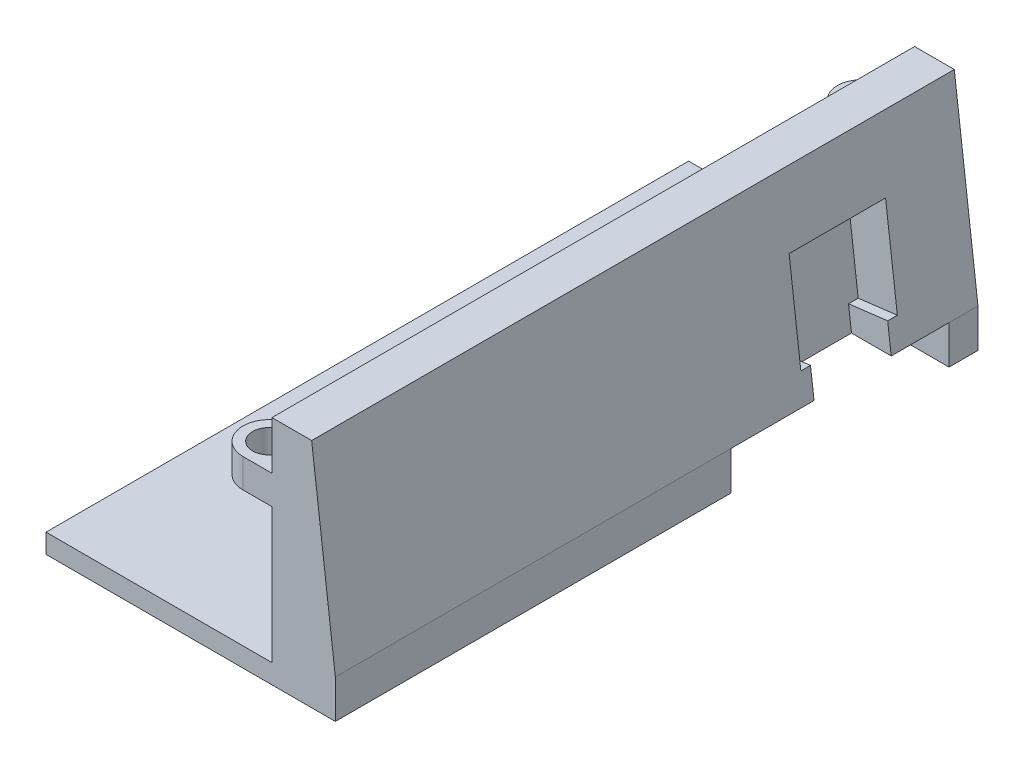
SolidWorks part; units mm, degrees
ref_plane "前视基准面" through (0, 0, 0) normal (0, 0, 1) x (1, 0, 0)
ref_plane "上视基准面" through (0, 0, 0) normal (0, 1, 0) x (1, 0, 0)
ref_plane "右视基准面" through (0, 0, 0) normal (1, 0, 0) x (0, 0, -1)
sketch "草图1" plane through (0, 0, 0) normal (0, 1, 0) x (1, 0, 0)
  line L0 (0, 0) -> (0, -61.38) construction
  line L2 (0, -58.63) -> (5, -58.63)
  line L3 (0, -58.63) -> (0, -64.13)
  line L4 (0, -64.13) -> (5, -64.13)
  line L5 (5, -58.63) -> (5, -64.13)
  line L6 (0, 2.5) -> (5, 2.5)
  line L7 (0, 2.5) -> (0, -2.5)
  line L8 (0, -2.5) -> (5, -2.5)
  line L9 (5, 2.5) -> (5, -2.5)
  line L10 (5, 2.5) -> (8, 2.5)
  line L11 (5, 2.5) -> (5, -64.13)
  line L12 (5, -64.13) -> (8, -64.13)
  line L13 (8, 2.5) -> (8, -64.13)
  circle A0 centre (0, 0) radius 1.75
  circle A1 centre (0, 0) radius 2.5
  circle A2 centre (0, -61.38) radius 1.75
  circle A3 centre (0, -61.38) radius 2.75
  dimension "D1" = 3.5
  dimension "D2" = 5
  dimension "D4" = 3.5
  dimension "D5" = 5.5
  dimension "D3" = 61.38
  dimension "D6" = 5
  dimension "D7" = 3
  dimension "D8" = 5.5
extrude "凸台-拉伸1" add sketch "草图1" along normal blind 3 contours L3 A3 A2 | L3 A3 A2 | A3 L4 L5 L2 | L13 L10 L9 L11 L5 L12 | L7 A1 A0 | L7 A1 A0 | A1 L8 L9 L6
ref_plane "基准面1" through (0, 0, 64.13) normal (0, 0, 1) x (1, 0, 0)
sketch "草图2" plane through (0, 0, 64.13) normal (0, 0, 1) x (1, 0, 0)
  line L0 (8, 3) -> (3, 3)
  line L1 (0, 3) -> (8, 3) construction
  line L2 (3, 3) -> (3, 31.3564)
  line L3 (3, 31.3564) -> (8, 3)
  line L4 (8, 3) -> (10.6449, -12)
  line L5 (10.6449, -12) -> (3, -12)
  line L6 (3, -12) -> (3, 3)
  line L7 (3, 8) -> (7.1184, 8)
  dimension "D1" = 5
  dimension "D2" = 5
  dimension "D3" = 15
  dimension "D4" = 80
extrude "凸台-拉伸2" add sketch "草图2" against normal through all contours L7 L2 L0 L3 | L6 L5 L4 L0
sketch "草图3" plane through (0, 0, 64.13) normal (0, 0, 1) x (1, 0, 0)
  line L0 (3, 8) -> (7.1184, 8)
  line L1 (7.1184, 8) -> (9.5741, -12)
  line L2 (10.6449, -12) -> (3, -12) construction
  line L3 (7.1184, 8) -> (7.998, 8.163)
  line L4 (7.998, 8.163) -> (13.1792, -12.892)
  line L5 (13.1792, -12.892) -> (10.468, -13.8884)
  line L6 (10.468, -13.8884) -> (9.5741, -12)
  dimension "D1" = 97
extrude "切除-拉伸1" cut sketch "草图3" against normal through all contours L6 L5 L4 L3 L1
ref_plane "基准面2" through (3.9231, 0.4817, 0) normal (0.9925, 0.1219, 0) x (0, 0, -1)
sketch "草图4" plane through (3.9231, 0.4817, 0) normal (0.9925, 0.1219, 0) x (0, 0, -1)
  line L0 (2.5, -13.0773) -> (-64.13, -13.0773) construction
  line L1 (-5.5, -0.0773) -> (-15.5, -0.0773)
  line L2 (-5.5, -0.0773) -> (-5.5, -10.0773)
  line L3 (-5.5, -10.0773) -> (-15.5, -10.0773)
  line L4 (-15.5, -0.0773) -> (-15.5, -10.0773)
  line L5 (-5.5, -0.0773) -> (-15.5, -10.0773) construction
  line L6 (-5.5, -10.0773) -> (-15.5, -0.0773) construction
  line L7 (-6.5, -7.0773) -> (-14.5, -7.0773)
  line L8 (-6.5, -7.0773) -> (-6.5, -13.0773)
  line L9 (-6.5, -13.0773) -> (-14.5, -13.0773)
  line L10 (-14.5, -7.0773) -> (-14.5, -13.0773)
  line L11 (-6.5, -7.0773) -> (-14.5, -13.0773) construction
  line L12 (-6.5, -13.0773) -> (-14.5, -7.0773) construction
  line L14 (2.5, 7.0729) -> (2.5, -13.0773) construction
  point P0 (-10.5, -5.0773)
  point P5 (-10.5, -10.0773)
  dimension "D1" = 10
  dimension "D2" = 10
  dimension "D3" = 8
  dimension "D4" = 6
  dimension "D5" = 8
extrude "切除-拉伸2" cut sketch "草图4" along normal blind 10 contours L10 L7 L8 L3 L2 L1 L4 | L7 L10 L3 L8 | L3 L10 L9 L8
ref_plane "基准面3" through (0, -12, 0) normal (0, -1, 0) x (-1, 0, 0)
sketch "草图5" plane through (0, -12, 0) normal (0, -1, 0) x (-1, 0, 0)
  line L0 (-3, 2.5) -> (-3, -64.13) construction
  line L1 (-9.5741, -64.13) -> (-3, -64.13)
  line L2 (-9.5741, -64.13) -> (-9.5741, -23.13)
  line L3 (-9.5741, -23.13) -> (-3, -23.13)
  line L4 (-3, -64.13) -> (-3, -23.13)
  line L6 (-9.5741, 2.5) -> (-3, 2.5)
  line L7 (-9.5741, 2.5) -> (-9.5741, -0.5)
  line L8 (-9.5741, -0.5) -> (-3, -0.5)
  line L9 (-3, 2.5) -> (-3, -0.5)
  dimension "D1" = 3
  dimension "D2" = 41
extrude "凸台-拉伸3" add sketch "草图5" along normal blind 2
ref_plane "基准面4" through (0, -14, 0) normal (0, -1, 0) x (-1, 0, 0)
sketch "草图6" plane through (0, -14, 0) normal (0, -1, 0) x (-1, 0, 0)
  line L1 (-9.5741, 2.5) -> (20.4259, 2.5)
  line L2 (-9.5741, 2.5) -> (-9.5741, -0.5)
  line L3 (-9.5741, -0.5) -> (20.4259, -0.5)
  line L4 (20.4259, 2.5) -> (20.4259, -0.5)
  line L5 (-9.5741, -64.13) -> (20.4259, -64.13)
  line L6 (-9.5741, -64.13) -> (-9.5741, -23.13)
  line L7 (-9.5741, -23.13) -> (20.4259, -23.13)
  line L8 (20.4259, -64.13) -> (20.4259, -23.13)
  line L9 (0.4259, -0.5) -> (20.4259, -0.5)
  line L10 (0.4259, -0.5) -> (0.4259, -23.13)
  line L11 (0.4259, -23.13) -> (20.4259, -23.13)
  line L12 (20.4259, -0.5) -> (20.4259, -23.13)
  dimension "D1" = 30
  dimension "D2" = 10
extrude "凸台-拉伸4" add sketch "草图6" along normal blind 2 contours L12 L3 L10 L7 | L5 L8 L7 L6 | L4 L1 L2 L3
